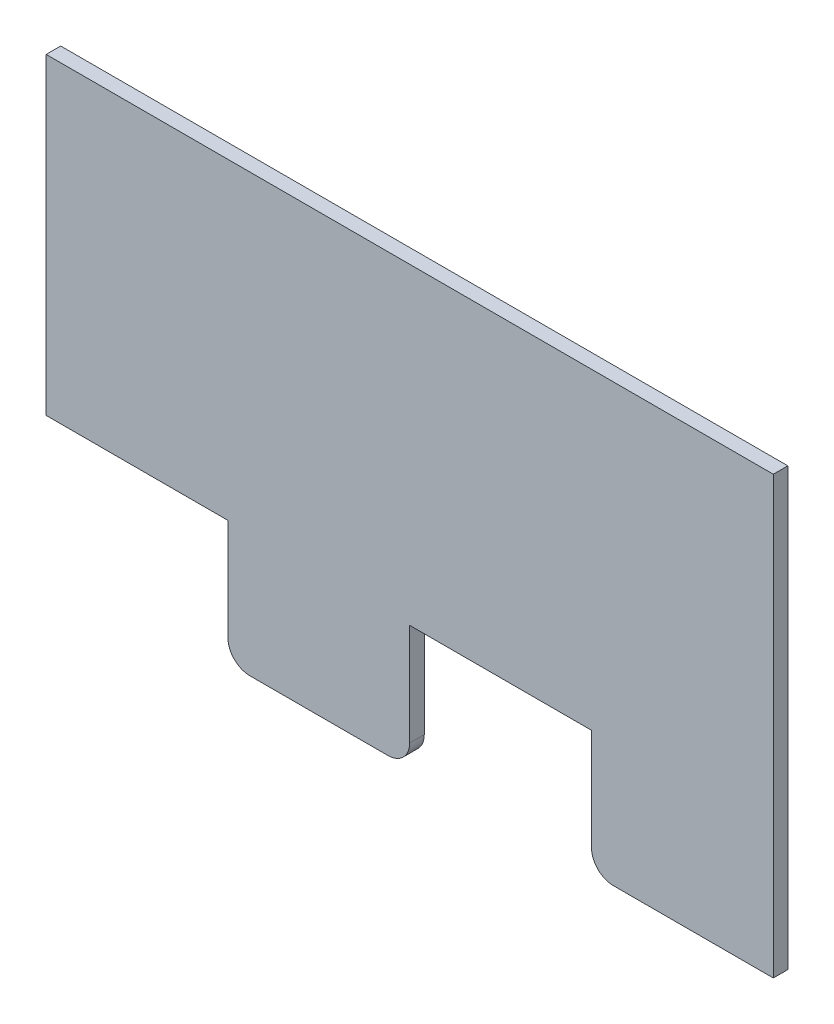
SolidWorks part; units mm, degrees
material "Hexcel AS4C (3000 Filaments)"
ref_plane "Front Plane" through (0, 0, 0) normal (0, 0, 1) x (1, 0, 0)
ref_plane "Top Plane" through (0, 0, 0) normal (0, 1, 0) x (1, 0, 0)
ref_plane "Right Plane" through (0, 0, 0) normal (1, 0, 0) x (0, 0, -1)
sketch "Sketch1" plane through (0, 0, 0) normal (0, 0, 1) x (1, 0, 0)
  line L0 (0, -3) -> (25, -3)
  line L1 (-22, -20) -> (-3, -20)
  line L2 (-50, -3) -> (-50, 40)
  line L3 (-50, 40) -> (50, 40)
  line L4 (50, -20) -> (50, 40)
  line L7 (-50, -3) -> (-25, -3)
  line L8 (-50, -3) -> (-50, -20)
  line L9 (-50, -20) -> (-25, -20)
  line L10 (-25, -3) -> (-25, -17)
  line L11 (-50, -3) -> (-25, -20) construction
  line L12 (-50, -20) -> (-25, -3) construction
  line L13 (0, -3) -> (0, -17)
  line L14 (0, -20) -> (25, -20)
  line L15 (25, -3) -> (25, -17)
  line L16 (0, -3) -> (25, -20) construction
  line L17 (0, -20) -> (25, -3) construction
  line L18 (28, -20) -> (50, -20)
  arc A0 (0, -17) -> (-3, -20) centre (-3, -17) cw
  arc A1 (-25, -17) -> (-22, -20) centre (-22, -17) ccw
  arc A2 (28, -20) -> (25, -17) centre (28, -17) cw
  point P0 (0, 0)
  point P6 (-37.5, -11.5)
  point P11 (12.5, -11.5)
  dimension "D1" = 3
  dimension "D2" = 3
extrude "Boss-Extrude1" add sketch "Sketch1" along normal blind 2 contours L0 L15 L1 L4 L3 L2 L7 L10 L13
